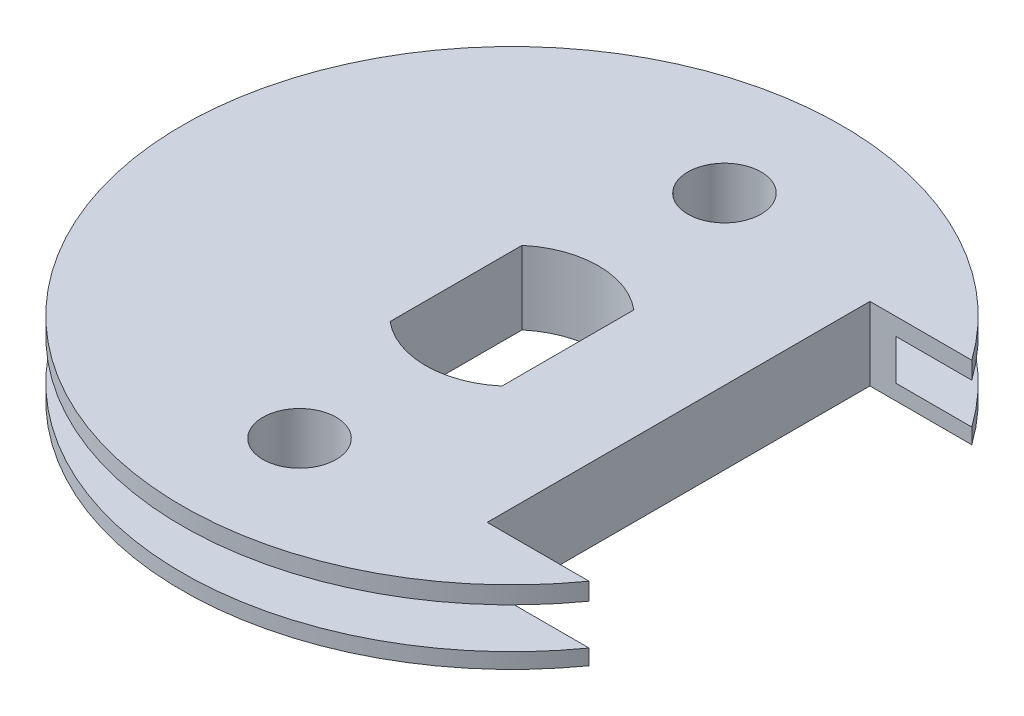
SolidWorks part; units mm, degrees
ref_plane "前视基准面" through (0, 0, 0) normal (0, 0, 1) x (1, 0, 0)
ref_plane "上视基准面" through (0, 0, 0) normal (0, 1, 0) x (1, 0, 0)
ref_plane "右视基准面" through (0, 0, 0) normal (1, 0, 0) x (0, 0, -1)
sketch "草图1" plane through (0, 0, 0) normal (0, 1, 0) x (1, 0, 0)
  line L0 (-1.5263, 1.8) -> (1.5263, 1.8)
  line L1 (0, 0) -> (-1.3415, 0) construction
  line L2 (-1.5263, -1.8) -> (1.5263, -1.8)
  arc A0 (-1.5263, 1.8) -> (-1.5263, -1.8) centre (0, 0) ccw
  arc A1 (1.5263, -1.8) -> (1.5263, 1.8) centre (0, 0) ccw
  circle A2 centre (0, 0) radius 9
  dimension "D1" = 1.8
extrude "凸台-拉伸3" add sketch "草图1" along normal blind 2 contours A2 A1 L2 A0 L0
sketch "草图2" plane through (0, 2, 0) normal (0, 1, 0) x (1, 0, 0)
  line L0 (-1.5263, 1.8) -> (1.5263, 1.8) construction
  line L1 (0, 0) -> (3.1135, 0) construction
  circle A0 centre (0, 5.8) radius 1
  circle A1 centre (0, -5.8) radius 1
  dimension "D1" = 4
extrude "切除-拉伸1" cut sketch "草图2" against normal blind 2
sketch "草图3" plane through (0, 0, 0) normal (0, 0, 1) x (1, 0, 0)
  line L0 (9, 1.5265) -> (8.0952, 1.5265)
  line L1 (9, 0) -> (9, 2) construction
  line L4 (8.0952, 0.4195) -> (9, 0.4195)
  line L5 (9, 0.4195) -> (9, 1.5265)
  line L6 (0, 0) -> (0, 0.824) construction
  line L7 (8.0952, 1.5265) -> (7.4091, 1.5265)
  line L8 (7.4091, 1.5265) -> (7.4091, 0.4195)
  line L9 (7.4091, 0.4195) -> (8.0952, 0.4195)
revolve "切除-旋转1" cut sketch "草图3" angle 360 about L6
sketch "草图4" plane through (0, 0, 0) normal (0, 1, 0) x (1, 0, 0)
  line L0 (8.7075, 5.2245) -> (5.9259, 5.2245)
  line L2 (0, 0) -> (1.935, 0) construction
  line L3 (8.7075, -5.2245) -> (5.9259, -5.2245)
  line L4 (8.7075, 5.2245) -> (10.5941, 5.2245)
  line L5 (10.5941, 5.2245) -> (10.5941, -5.2245)
  line L6 (10.5941, -5.2245) -> (8.7075, -5.2245)
  line L7 (5.9259, 5.2245) -> (4.5472, 5.2245)
  line L8 (4.5472, 5.2245) -> (4.5472, -5.2245)
  line L9 (4.5472, -5.2245) -> (5.9259, -5.2245)
  point P7 (5.9259, 0)
extrude "切除-拉伸2" cut sketch "草图4" along normal blind 4
sketch "草图5" plane through (0, 2, 0) normal (0, 1, 0) x (1, 0, 0)
  line L0 (1.5263, 1.8) -> (1.5263, -1.8)
  line L1 (-1.5263, 1.8) -> (-1.5263, -1.8)
  arc A0 (-1.5263, -1.8) -> (1.5263, -1.8) centre (0, 0) ccw
  arc A1 (1.5263, 1.8) -> (-1.5263, 1.8) centre (0, 0) ccw
sketch "草图6" plane through (0, 2, 0) normal (0, 1, 0) x (1, 0, 0)
  line L0 (-1.5263, 1.8) -> (-3.0369, 1.8)
  line L1 (-1.5263, -1.8) -> (-3.0369, -1.8)
  line L2 (-3.0369, -1.8) -> (-3.0369, 1.8)
  line L3 (0, 0) -> (0, 2.9992) construction
  line L4 (1.5263, -1.8) -> (3.0369, -1.8)
  line L5 (3.0369, -1.8) -> (3.0369, 1.8)
  line L6 (1.5263, 1.8) -> (3.0369, 1.8)
  line L7 (-1.5263, 1.8) -> (-1.5263, -1.8)
  line L8 (1.5263, 1.8) -> (1.5263, -1.8)
extrude "凸台-拉伸4" add sketch "草图6" against normal blind 2
extrude "切除-拉伸3" cut sketch "草图5" against normal blind 2
